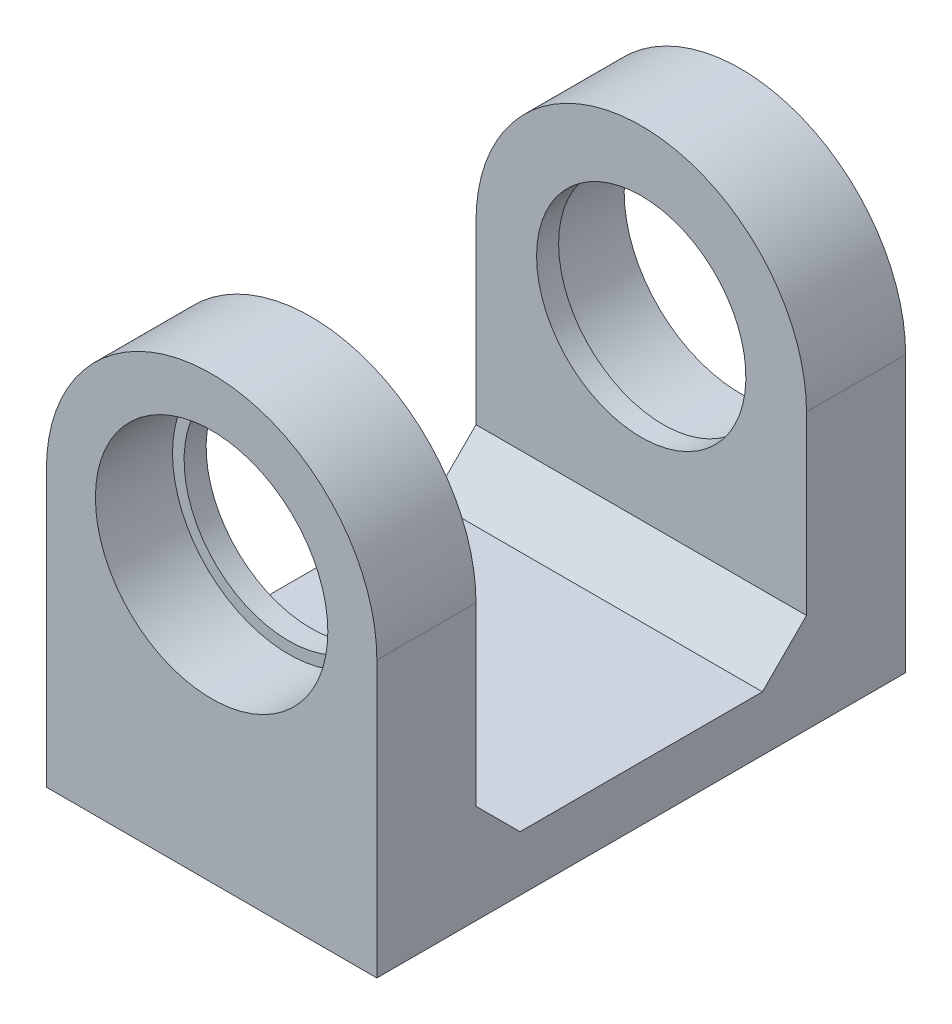
SolidWorks part; units mm, degrees
material "6061 合金"
ref_plane "前视基准面" through (0, 0, 0) normal (0, 0, 1) x (1, 0, 0)
ref_plane "上视基准面" through (0, 0, 0) normal (0, 1, 0) x (1, 0, 0)
ref_plane "右视基准面" through (0, 0, 0) normal (1, 0, 0) x (0, 0, -1)
sketch "草图1" plane through (0, 0, 0) normal (0, 0, 1) x (1, 0, 0)
  line L0 (-15, -25) -> (-15, 0)
  line L3 (-15, -25) -> (15, -25)
  line L7 (15, -25) -> (15, 0)
  arc A0 (15, 0) -> (-15, 0) centre (0, 0) ccw
  circle A1 centre (0, 0) radius 9.5
  dimension "D2" = 30
  dimension "D1" = 25
extrude "凸台-拉伸1" add sketch "草图1" along normal mid plane 48
sketch "草图2" plane through (0, 0, 0) normal (1, 0, 0) x (0, 0, -1)
  line L0 (-24, 0) -> (24, 0) construction
  line L1 (0, 55) -> (0, -55) construction
  line L2 (-24, -25) -> (24, -25) construction
  line L4 (-15, 49.95) -> (15, 49.95)
  line L5 (-15, 49.95) -> (-15, -20)
  line L6 (-15, -20) -> (15, -20)
  line L7 (15, 49.95) -> (15, -20)
  line L14 (-30, -20) -> (0, -25) construction
  point P6 (-30, 4.975)
  dimension "D1" = 30
  dimension "D2" = 20
  dimension "D3" = 15
extrude "切除-拉伸1" cut sketch "草图2" against normal through all both and the other way through all
sketch "草图4" plane through (0, 0, -24) normal (0, 0, -1) x (-1, 0, 0)
  circle A0 centre (0, 0) radius 10.55
  dimension "D1" = 21.1
extrude "切除-拉伸3" cut sketch "草图4" against normal blind 7
chamfer "倒角2" distance 4 angle 45 2 edges at (0, -20, -15) (0, -20, 15)
hole_wizard "M3 螺纹孔1" positions "草图7" profile "草图6" tap size "M3" standard "GB"
sketch "草图7" plane through (0, -25, 0) normal (0, -1, 0) x (-1, 0, 0)
  line L0 (15, -24) -> (15, 24) construction
  line L1 (-15, -24) -> (-15, 24) construction
  line L2 (15, 24) -> (-15, 24) construction
  line L3 (15, -24) -> (-15, -24) construction
  point P0 (9, -19)
  point P2 (-9, -19)
  point P4 (9, 19)
  point P6 (-9, 19)
  dimension "D1" = 6
  dimension "D2" = 6
  dimension "D3" = 6
  dimension "D4" = 6
  dimension "D5" = 5
  dimension "D6" = 5
  dimension "D7" = 5
  dimension "D8" = 5
sketch "草图6" plane through (-9, -25, 19) normal (1, 0, 0) x (0, 0, -1)
  line L0 (0, 0) -> (0, 10.7511)
  line L1 (0, 10.7511) -> (1.25, 10)
  line L2 (1.25, 10) -> (1.25, 0)
  line L5 (1.25, 0) -> (0, 0)
  line L10 (0, 10.7511) -> (-1.25, 10) construction
  line L11 (0, -6.35) -> (0, 107.95) construction
  dimension "螺纹孔钻头直径" = 2.5
  dimension "螺纹孔钻头深度" = 10
  dimension "导头角度" = 118
cosmetic thread "孔螺蚊线1" parameters "D1"=10, "D2"=3
cosmetic thread "孔螺蚊线2" parameters "D1"=10, "D2"=3
cosmetic thread "孔螺蚊线3" parameters "D1"=10, "D2"=3
cosmetic thread "孔螺蚊线4" parameters "D1"=10, "D2"=3
mirror "镜向1" about plane through (0, 0, 0) normal (0, 0, 1) of "切除-拉伸3"
